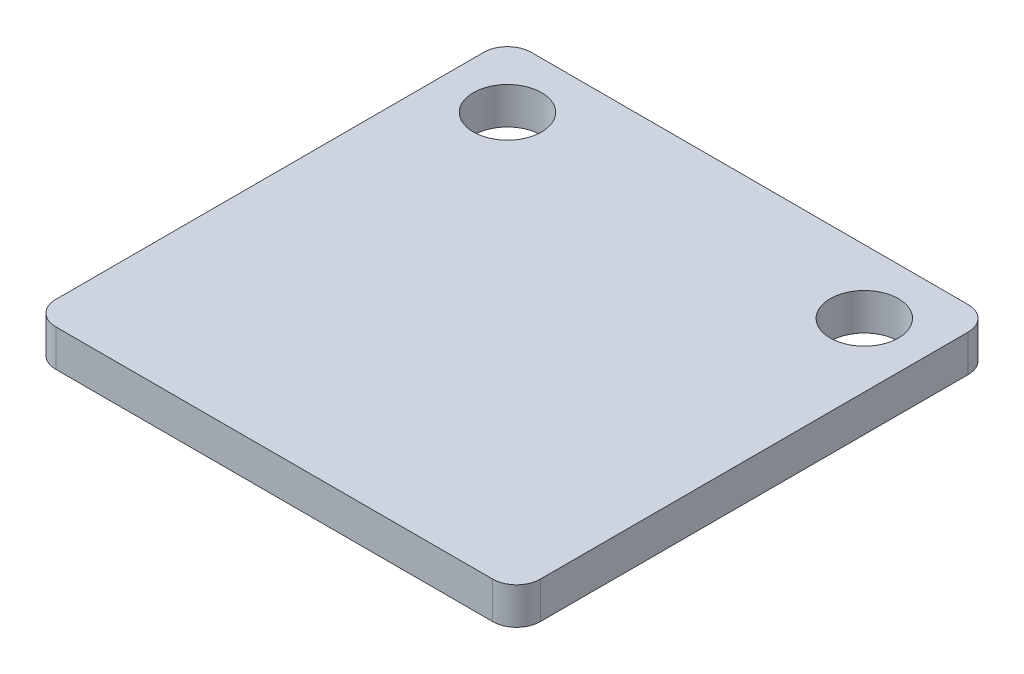
SolidWorks part; units mm, degrees
ref_plane "Front Plane" through (0, 0, 0) normal (0, 0, 1) x (1, 0, 0)
ref_plane "Top Plane" through (0, 0, 0) normal (0, 1, 0) x (1, 0, 0)
ref_plane "Right Plane" through (0, 0, 0) normal (1, 0, 0) x (0, 0, -1)
sketch "Sketch1" plane through (0, 0, 0) normal (0, 1, 0) x (1, 0, 0)
  line L1 (-10.19, -10) -> (10.19, -10)
  line L2 (-10.19, -10) -> (-10.19, 10)
  line L3 (-10.19, 10) -> (10.19, 10)
  line L4 (10.19, -10) -> (10.19, 10)
  line L5 (-10.19, -10) -> (10.19, 10) construction
  line L6 (-10.19, 10) -> (10.19, -10) construction
  point P0 (0, 0)
  dimension "D1" = 20
  dimension "D2" = 20.38
extrude "Boss-Extrude1" add sketch "Sketch1" along normal mid plane 1.55
sketch "Sketch2" plane through (0, 0.775, 0) normal (0, 1, 0) x (1, 0, 0)
  line L0 (-10.19, 10) -> (-7.505, 7.315) construction
  line L2 (7.505, 7.315) -> (10.19, 10) construction
  line L3 (-8.94, 7.315) -> (-10.19, 7.315) construction
  line L4 (-10.19, 10) -> (-10.19, -10) construction
  circle A0 centre (-7.505, 7.315) radius 1.435
  circle A1 centre (7.505, 7.315) radius 1.435
  dimension "D2" = 2.87
  dimension "D1" = 1.25
extrude "Cut-Extrude1" cut sketch "Sketch2" against normal through all both and the other way through all
fillet "Fillet1" radius 1 4 edges at (10.19, 0, 10) (-10.19, 0, 10) (10.19, 0, -10) (-10.19, 0, -10)
sketch "Sketch3" plane through (0, -0.775, 0) normal (0, -1, 0) x (-1, 0, 0)
  line L1 (-1, -1.28) -> (1, -1.28)
  line L2 (-1, -1.28) -> (-1, 1.28)
  line L3 (-1, 1.28) -> (1, 1.28)
  line L4 (1, -1.28) -> (1, 1.28)
  line L5 (-1, -1.28) -> (1, 1.28) construction
  line L6 (-1, 1.28) -> (1, -1.28) construction
  point P0 (0, 0)
  dimension "D1" = 2.56
  dimension "D2" = 2
extrude "Boss-Extrude2" add sketch "Sketch3" along normal blind 0.5
